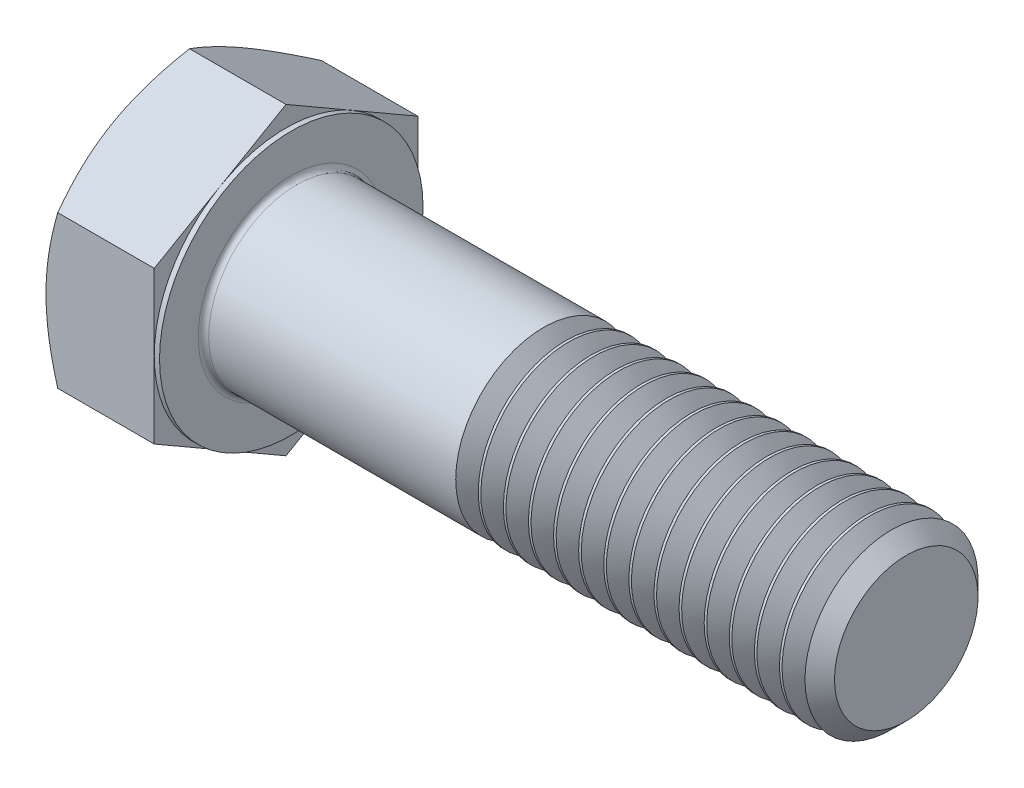
SolidWorks part; units mm, degrees
extrude "BaseHead" add sketch "Sketch1" along normal blind 8.2042
sketch "Sketch1" plane through (0, 0, 0) normal (1, 0, 0) x (0, 0, -1)
  line L0 (9.525, 5.4993) -> (9.525, -5.4993)
  line L1 (-9.525, 5.4993) -> (-9.525, -5.4993)
  line L2 (9.525, -5.4993) -> (0, -10.9985)
  line L3 (0, -10.9985) -> (-9.525, -5.4993)
  line L4 (9.525, 5.4993) -> (0, 10.9985)
  line L5 (0, 10.9985) -> (-9.525, 5.4993)
  dimension "Width_flats" = 19.05
  dimension "D2" = 120
  dimension "D3" = 9.525
  dimension "D4" = 9.525
  dimension "D5" = 9.525
revolve "HeadChamfer" cut sketch "Sketch3" angle 360 about L6
sketch "Sketch3" plane through (0, 0, 0) normal (0, 0, 1) x (1, 0, 0)
  line L0 (0, 9.525) -> (4.5169, 17.3485)
  line L1 (0, 10.9985) -> (0, 5.4993) construction
  line L2 (4.5169, 17.3485) -> (4.5169, 23.6985)
  line L3 (4.5169, 23.6985) -> (-12.7, 23.6985)
  line L4 (-12.7, 23.6985) -> (-12.7, 9.525)
  line L5 (-12.7, 9.525) -> (0, 9.525)
  line L6 (0, 0) -> (99.06, 0) construction
  line L7 (8.2042, 10.9985) -> (0, 10.9985) construction
  dimension "D1" = 9.525
  dimension "D2" = 6.35
  dimension "D3" = 12.7
  dimension "D4" = 6.35
  dimension "Head_ch_ang" = 30
material "Plain Carbon Steel"
ref_plane "Plane1" through (0, 0, 0) normal (0, 0, 1) x (1, 0, 0)
ref_plane "Plane2" through (0, 0, 0) normal (0, 1, 0) x (1, 0, 0)
ref_plane "Plane3" through (0, 0, 0) normal (1, 0, 0) x (0, 0, -1)
sketch "BodySke" plane through (0, 0, 0) normal (0, 0, 1) x (1, 0, 0)
  line L0 (0, 5.4993) -> (0, -5.4993) construction
  line L1 (0, 0) -> (52.6542, 0)
  line L2 (0, 0) -> (0, 6.35)
  line L3 (0, 6.35) -> (51.4909, 6.35)
  line L4 (52.6542, 0) -> (52.6542, 5.1867)
  line L5 (8.2042, 10.9985) -> (8.2042, 5.4993) construction
  line L6 (52.6542, 5.1867) -> (51.4909, 6.35)
  line L7 (0, 0) -> (96.52, 0) construction
  line L8 (52.6542, -5.1867) -> (51.4909, -6.35) construction
  line L9 (0, -6.35) -> (51.4909, -6.35) construction
  line L10 (10.1575, 15.24) -> (10.1575, -1.27) construction
  line L11 (27.2542, 15.24) -> (27.2542, -1.27) construction
  line L12 (8.2042, 5.4993) -> (8.2042, -5.4993) construction
  dimension "Diameter" = 12.7
revolve "BaseBody" add sketch "BodySke" angle 360 about L7
cosmetic thread "ThreadCosmetic" [suppressed]
sketch "Sketch4" plane through (0, 0, 0) normal (0, 0, 1) x (1, 0, 0)
  line L1 (8.2042, 10.9985) -> (8.2042, 5.4993) construction
  line L2 (8.2042, 9.525) -> (7.8232, 9.525)
  line L3 (8.2042, 9.525) -> (8.2042, 36.3985)
  line L4 (8.2042, 36.3985) -> (7.8232, 36.3985)
  line L5 (0, 0) -> (95.25, 0) construction
  line L6 (0, 0) -> (96.52, 0) construction
  line L7 (7.8232, 9.525) -> (7.8232, 36.3985)
  line L8 (8.2042, 10.9985) -> (0.8507, 10.9985) construction
  dimension "D1" = 9.525
  dimension "D2" = 25.4
revolve "BearingFace" cut sketch "Sketch4" angle 360 about L5
fillet "HeadFillet" radius 0.381 1 edges at (8.2042, 0, -6.35)
sketch "ThdSchSke" plane through (0, 0, 0) normal (0, 0, 1) x (1, 0, 0)
  line L0 (27.2542, -5.1867) -> (26.4396, -6.35)
  line L1 (27.2542, -5.1867) -> (28.0688, -6.35)
  line L2 (28.0688, -6.35) -> (28.0688, -7.9375)
  line L3 (-3.175, 0) -> (5.1513, 0) construction
  line L5 (28.0688, -7.9375) -> (26.4396, -7.9375)
  line L6 (26.4396, -7.9375) -> (26.4396, -6.35)
  dimension "Thread_minor" = 10.3734
  dimension "Diameter" = 12.7
  dimension "Start" = 27.2542
revolve "ThreadSchematic" cut sketch "ThdSchSke" angle 360 about L3
pattern_linear "ThdSchPat" count 14 spacing 1.8143 along (1, 0, 0) of "ThreadSchematic"
equation "\"D3@Sketch1\" = \"Width_flats@Sketch1\" / 2"
equation "\"D4@Sketch1\" = \"D3@Sketch1\""
equation "\"D5@Sketch1\" = \"D4@Sketch1\""
equation "\"Thread_minor@ThreadCosmetic\" = \"Minor_dia@BodySke\""
equation "\"D1@Sketch3\" = \"Width_flats@Sketch1\" / 2"
equation "\"D1@Sketch4\" = \"Width_flats@Sketch1\" / 2"
equation "\"Thread_length@ThreadCosmetic\" = ((sgn( (\"Length@BodySke\" - \"Advance@BodySke\" ) - \"Thread_nom@BodySke\" )-1)*( (\"Length@BodySke\" - \"Advance@BodySke\" ) - \"Thread_nom@BodySke\" ))/-2+ \"Thread_nom@BodySke\""
equation "\"Thread_minor@ThdSchSke\" = \"Minor_dia@BodySke\""
equation "\"Diameter@ThdSchSke\" = \"Diameter@BodySke\""
equation "\"Overcut@ThdSchSke\" = \"Diameter@BodySke\" * 1.25"
equation "\"Start@ThdSchSke\" = \"Head_ht@BaseHead\" + \"Length@BodySke\" - \"Thread_length@ThreadCosmetic\"  '---Non-countersunk---"
equation "\"Num_threads@ThdSchPat\" = int( \"Thread_length@ThreadCosmetic\" / \"Advance@BodySke\" + 0.999 )  + 1"
equation "\"Advance@ThdSchPat\" = \"Thread_length@ThreadCosmetic\" /  (\"Num_threads@ThdSchPat\" - 1) 'relax it"
equation "\"Num_threads@ThdSchPat\" = \"Num_threads@ThdSchPat\" - sgn( \"Num_threads@ThdSchPat\" - 1) '---chamfered tips only---"
